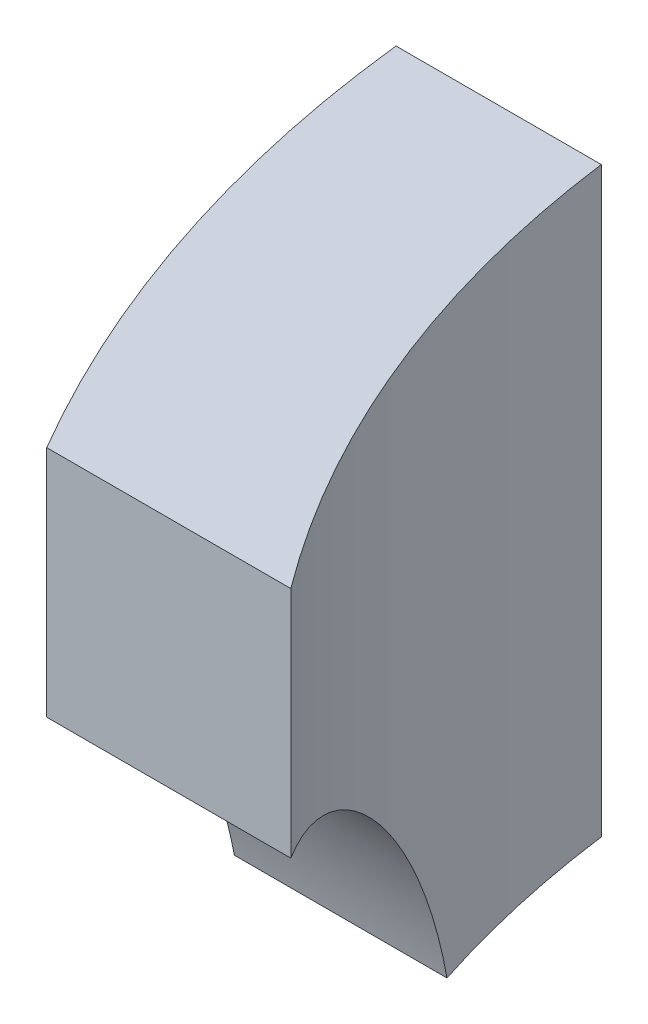
SolidWorks part; units mm, degrees
ref_plane "Front Plane" through (0, 0, 0) normal (0, 0, 1) x (1, 0, 0)
ref_plane "Top Plane" through (0, 0, 0) normal (0, 1, 0) x (1, 0, 0)
ref_plane "Right Plane" through (0, 0, 0) normal (1, 0, 0) x (0, 0, -1)
sketch "Sketch1" plane through (0, 0, 0) normal (0, 1, 0) x (1, 0, 0)
  line L0 (-1000, 0) -> (-104.805, 0) construction
  line L1 (0, -1000) -> (0, 49000) construction
  line L2 (91.805, -10) -> (90.2527, -10)
  line L3 (-76.805, 0) -> (76.805, 0)
  line L7 (-91.805, -10) -> (-90.2527, -10)
  line L9 (104.805, 0) -> (49000, 0) construction
  line L10 (-76.805, 0) -> (-76.805, 20)
  line L12 (-76.805, 0) -> (76.805, 0) construction
  line L13 (91.805, 20) -> (91.805, -10)
  line L14 (76.805, 20) -> (91.805, 20)
  line L17 (-76.805, 20) -> (-91.805, 20)
  line L18 (76.805, 0) -> (76.805, 20)
  line L19 (-91.805, 20) -> (-91.805, -10)
  arc A0 (-90.2527, -10) -> (90.2527, -10) centre (0, 0) ccw
  arc A1 (-76.805, 0) -> (76.805, 0) centre (0, 0) ccw
  dimension "D1" = 181.61
  dimension "D2" = 14
  dimension "D3" = 30
  dimension "D4" = 15
extrude "Boss-Extrude1" add sketch "Sketch1" against normal blind 60
sketch "Sketch25" plane through (0, -60, 0) normal (0, -1, 0) x (-1, 0, 0)
  line L0 (76.805, 20) -> (91.805, -10)
  line L1 (91.805, -10) -> (76.805, -10)
  line L2 (76.805, -10) -> (91.805, 20)
  line L3 (-91.805, -10) -> (-76.805, 20)
  line L4 (81.555, -3.5) -> (87.055, -3.5)
  line L5 (81.555, -3.5) -> (81.555, 13.5)
  line L6 (81.555, 13.5) -> (87.055, 13.5)
  line L7 (87.055, -3.5) -> (87.055, 13.5)
  line L8 (81.555, -3.5) -> (87.055, 13.5) construction
  line L9 (81.555, 13.5) -> (87.055, -3.5) construction
  line L10 (-76.805, 20) -> (-77.8097, -10)
  line L11 (-77.8097, -10) -> (-91.805, -10)
  line L12 (-77.8097, -10) -> (-91.805, 20)
  line L14 (-87.055, -3.5) -> (-81.555, -3.5)
  line L15 (-87.055, -3.5) -> (-87.055, 13.5)
  line L16 (-87.055, 13.5) -> (-81.555, 13.5)
  line L17 (-81.555, -3.5) -> (-81.555, 13.5)
  line L18 (-87.055, -3.5) -> (-81.555, 13.5) construction
  line L19 (-87.055, 13.5) -> (-81.555, -3.5) construction
  point P4 (84.305, 5)
  point P16 (-84.305, 5)
  dimension "D1" = 5.5
  dimension "D2" = 17
  dimension "D3" = 17
  dimension "D4" = 5.5
extrude "Boss-Extrude3" add sketch "Sketch25" along normal blind 20 contours L15 L16 L17 L14 | L5 L6 L7 L4
ref_plane "Plane4" through (0, 0, 90) normal (0, 0, 1) x (1, 0, 0)
fillet "Fillet1" radius 2.3 8 edges at (84.305, -60, 3.5) (81.555, -60, -5) (84.305, -60, -13.5) (87.055, -60, -5) (-87.055, -60, -5) (-84.305, -60, -13.5) (-84.305, -60, 3.5) (-81.555, -60, -5)
sketch "Sketch28" plane through (91.805, 0, 0) normal (1, 0, 0) x (0, 0, -1)
  line L2 (20, 0) -> (20, -60)
  line L3 (20, -60) -> (-10, -60)
  line L4 (-10, 0) -> (-10, -60)
  line L5 (9, -37) -> (1, -37)
  line L6 (9, -37) -> (9, -47)
  line L7 (9, -47) -> (1, -47)
  line L8 (1, -37) -> (1, -47)
  line L9 (9, -37) -> (1, -47) construction
  line L10 (9, -47) -> (1, -37) construction
  point P7 (5, -42)
  dimension "D1" = 11
  dimension "D2" = 8
  dimension "D3" = 10
  dimension "D4" = 13
extrude "Cut-Extrude17" cut sketch "Sketch28" against normal blind 265 contours L5 L8 L7 L6
sketch "Sketch30" plane through (0, 0, -20) normal (0, 0, -1) x (-1, 0, 0)
  line L0 (-91.805, -60) -> (-91.805, 0) construction
  line L1 (91.805, 0) -> (-91.805, 0)
  line L2 (91.805, 0) -> (91.805, -30)
  line L3 (91.805, -30) -> (-91.805, -30)
  line L4 (-91.805, 0) -> (-91.805, -30)
  dimension "D1" = 30
extrude "Cut-Extrude19" cut sketch "Sketch30" against normal through all both and the other way through all
sketch "Sketch32" plane through (0, 0, -20) normal (0, 0, -1) x (-1, 0, 0)
  line L9 (0, 0) -> (0, -102.7115)
  line L10 (53.2739, -37) -> (53.2739, -51)
  line L11 (-66.6352, -37) -> (-63.6352, -37)
  line L12 (-66.6352, -37) -> (-66.6352, -51)
  line L13 (-66.6352, -51) -> (-63.6352, -51)
  line L14 (-63.6352, -37) -> (-63.6352, -51)
  line L15 (-50.2739, -37) -> (-53.2739, -37)
  line L16 (-50.2739, -37) -> (-50.2739, -51)
  line L17 (-50.2739, -51) -> (-53.2739, -51)
  line L18 (-53.2739, -37) -> (-53.2739, -51)
  line L19 (50.2739, -51) -> (53.2739, -51)
  line L20 (50.2739, -37) -> (50.2739, -51)
  line L21 (50.2739, -37) -> (53.2739, -37)
  line L22 (63.6352, -37) -> (63.6352, -51)
  line L23 (66.6352, -51) -> (63.6352, -51)
  line L24 (66.6352, -37) -> (66.6352, -51)
  line L25 (66.6352, -37) -> (63.6352, -37)
  point P19 (-51.7739, -37)
  point P20 (-65.1352, -37)
  dimension "D5" = 1.5
  dimension "D6" = 1.5
extrude "Cut-Extrude20" cut sketch "Sketch32" against normal through all both and the other way through all contours L14 L11 L12 L13 | L15 L18 L17 L16
ref_plane "Plane5" through (0, -110, 0) normal (0, -1, 0) x (-1, 0, 0)
sketch "Sketch40" plane through (-87.055, 0, 0) normal (-1, 0, 0) x (0, 0, 1)
  line L1 (-20, -30) -> (9.771, -30)
  line L2 (-20, -30) -> (-20, -92.0536)
  line L3 (-20, -92.0536) -> (9.771, -92.0536)
  line L4 (9.771, -30) -> (9.771, -92.0536)
extrude "Cut-Extrude23" cut sketch "Sketch40" against normal blind 254 and the other way blind 44
sketch "Sketch41" plane through (0, 0, 9.771) normal (0, 0, -1) x (-1, 0, 0)
  line L0 (-91.805, -30) -> (-91.805, -60) construction
  line L1 (-76.1809, -30) -> (-91.805, -30)
  line L2 (-76.1809, -30) -> (-76.1809, -45)
  line L3 (-76.1809, -45) -> (-91.805, -45)
  line L4 (-91.805, -30) -> (-91.805, -45)
  line L5 (-76.1809, -30) -> (-91.805, -45)
  line L6 (-91.805, -29.363) -> (-76.1809, -45)
  line L7 (-91.805, -60) -> (-76.1809, -60)
  line L8 (-76.1809, -60) -> (-91.805, -45)
  line L9 (-76.1809, -45) -> (-91.805, -60)
  line L10 (0, 0) -> (0, -83.1198)
  circle A0 centre (-83.993, -37.5) radius 3
  circle A1 centre (-83.993, -52.5) radius 3
  circle A2 centre (83.993, -52.5) radius 3
  circle A3 centre (83.993, -37.5) radius 3
  dimension "D1" = 6
  dimension "D2" = 6
extrude "Cut-Extrude24" cut sketch "Sketch41" against normal blind 254 contours A0 | A1 | A2 | A3
sketch "Sketch33" plane through (0, -60, 0) normal (0, -1, 0) x (-1, 0, 0)
  line L0 (90.2527, -10) -> (76.1512, -10)
  line L2 (73.8985, -52.7689) -> (61.5906, -45.8869)
  arc A0 (-76.1809, -9.771) -> (76.1809, -9.771) centre (0, 0) ccw construction
  arc A1 (76.1512, -10) -> (61.5906, -45.8869) centre (0, 0) cw
  arc A2 (90.2527, -10) -> (73.8985, -52.7689) centre (0, 0) cw
  arc A3 (-90.2527, -10) -> (90.2527, -10) centre (0, 0) ccw construction
extrude "Boss-Extrude4" add sketch "Sketch33" along normal blind 40
sketch "Sketch35" plane through (0, 0, 10) normal (0, 0, -1) x (-1, 0, 0)
  line L0 (90.2527, -100) -> (75.2527, -100)
  dimension "D1" = 15
sketch "Sketch37" plane through (0, 0, 0) normal (1, 0, 0) x (0, 0, -1)
  line L0 (-0.8813, -100) -> (-23.6906, -100)
  line L1 (-45.8869, -59.9172) -> (-45.8869, -76.0376)
  line L2 (-45.8869, -59.9172) -> (-66.9482, -59.9172)
  line L3 (-66.9482, -59.9172) -> (-63.7464, -92.4419)
  line L4 (-63.7464, -92.4419) -> (-47.5718, -115.3465)
  line L5 (-47.5718, -115.3465) -> (-8.0864, -115.3465)
  line L6 (-8.0864, -115.3465) -> (-0.8813, -100)
  line L7 (-45.8869, -100) -> (-10, -100) construction
  line L8 (-45.8869, -100) -> (-45.8869, -60) construction
  arc A0 (-23.6906, -100) -> (-45.8869, -76.0376) centre (-56.36, -108.0002) ccw
extrude "Cut-Extrude21" cut sketch "Sketch37" against normal blind 90 contours L6 L0 A0 L1 L2 L3 L4 L5
sketch "Sketch38" plane through (0, 0, 0) normal (1, 0, 0) x (0, 0, -1)
  line L0 (-90.805, -60) -> (-10, -60) construction
  line L1 (20, -30) -> (-90.805, -30)
  line L2 (20, -30) -> (20, -60)
  line L3 (-10, -60) -> (-90.805, -60)
  line L4 (-90.805, -30) -> (-90.805, -60)
  line L5 (-90.805, -30) -> (-90.805, -60) construction
  line L6 (-10, -100) -> (-10, -60) construction
  line L8 (20, -60) -> (20, -100)
  line L9 (20, -100) -> (-10, -100)
  line L10 (-10, -60) -> (-10, -100)
extrude "Cut-Extrude22" cut sketch "Sketch38" against normal through all both and the other way through all
